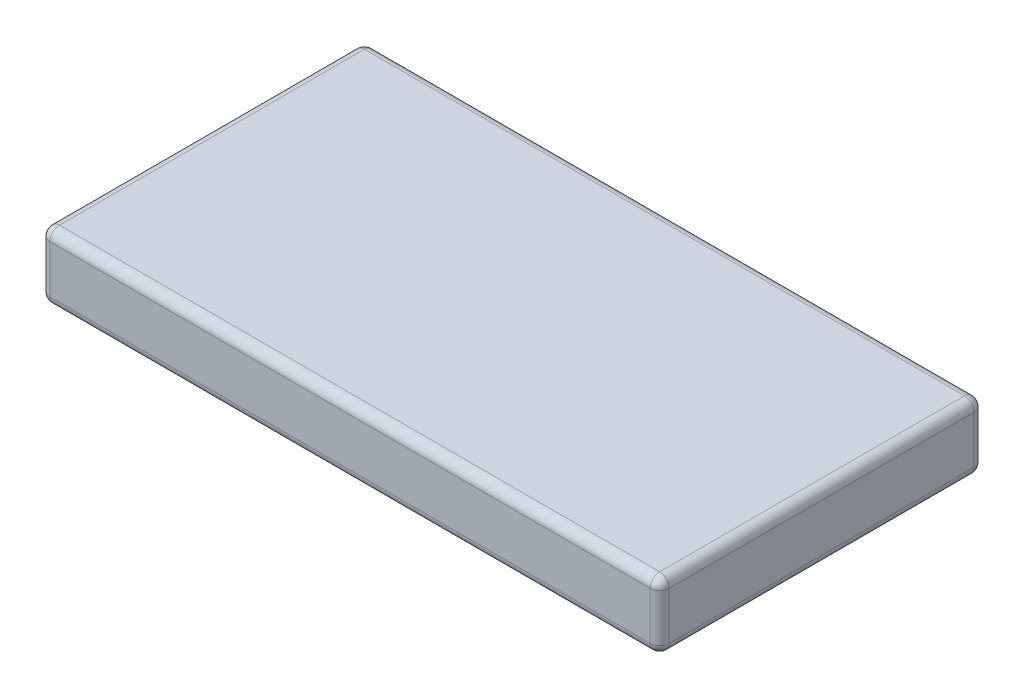
SolidWorks part; units mm, degrees
ref_plane "Front Plane" through (0, 0, 0) normal (0, 0, 1) x (1, 0, 0)
ref_plane "Top Plane" through (0, 0, 0) normal (0, 1, 0) x (1, 0, 0)
ref_plane "Right Plane" through (0, 0, 0) normal (1, 0, 0) x (0, 0, -1)
sketch "Sketch1" plane through (0, 0, 0) normal (0, 1, 0) x (1, 0, 0)
  line L1 (-32.5, 17) -> (32.5, 17)
  line L2 (-32.5, 17) -> (-32.5, -17)
  line L3 (-32.5, -17) -> (32.5, -17)
  line L4 (32.5, 17) -> (32.5, -17)
  line L5 (-32.5, 17) -> (32.5, -17) construction
  line L6 (-32.5, -17) -> (32.5, 17) construction
  point P0 (0, 0)
  dimension "D1" = 34
  dimension "D2" = 65
extrude "Boss-Extrude1" add sketch "Sketch1" along normal blind 7
fillet "Fillet1" radius 1 12 edges at (-32.5, 3.5, -17) (32.5, 3.5, -17) (-32.5, 7, 0) (0, 7, -17) (32.5, 7, 0) (-32.5, 3.5, 17) (0, 7, 17) (32.5, 3.5, 17) (0, 0, -17) (-32.5, 0, 0) (0, 0, 17) (32.5, 0, 0)
